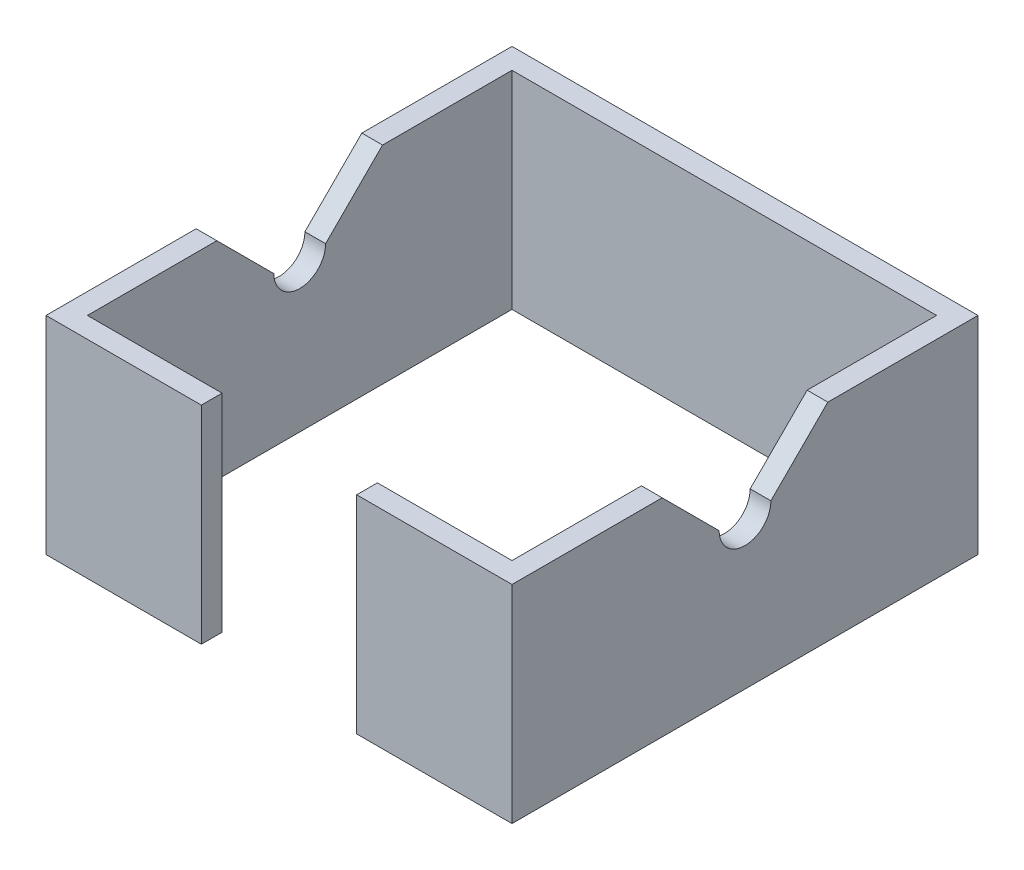
SolidWorks part; units mm, degrees
ref_plane "Přední rovina" through (0, 0, 0) normal (0, 0, 1) x (1, 0, 0)
ref_plane "Horní rovina" through (0, 0, 0) normal (0, 1, 0) x (1, 0, 0)
ref_plane "Pravá rovina" through (0, 0, 0) normal (1, 0, 0) x (0, 0, -1)
sketch "Skica1" plane through (0, 0, 0) normal (0, 1, 0) x (1, 0, 0)
  line L0 (2, -2) -> (43, -2)
  line L1 (0, 0) -> (45, 0)
  line L2 (0, 0) -> (0, -45)
  line L3 (0, -45) -> (45, -45)
  line L4 (45, 0) -> (45, -45)
  line L5 (43, -2) -> (43, -43)
  line L6 (2, -43) -> (43, -43)
  line L7 (2, -2) -> (2, -43)
  dimension "D1" = 45
  dimension "D2" = 45
  dimension "D3" = 2
extrude "Přidat vysunutím1" add sketch "Skica1" along normal blind 20
sketch "Skica2" plane through (0, 0, 45) normal (0, 0, 1) x (1, 0, 0)
  line L0 (0, 0) -> (45, 20) construction
  line L1 (45, 20) -> (45, 0) construction
  line L2 (0, 20) -> (45, 20) construction
  line L3 (0, 20) -> (45, 0) construction
  line L4 (0, 0) -> (45, 0) construction
  line L5 (15, 20) -> (30, 20)
  line L6 (15, 20) -> (15, 0)
  line L7 (15, 0) -> (30, 0)
  line L8 (30, 20) -> (30, 0)
  line L9 (15, 20) -> (30, 0) construction
  line L10 (15, 0) -> (30, 20) construction
  point P11 (22.5, 10)
  dimension "D1" = 15
extrude "Odebrat vysunutím1" cut sketch "Skica2" against normal up to next
sketch "Skica3" plane through (0, 0, 0) normal (-1, 0, 0) x (0, 0, 1)
  line L0 (22.5, 20) -> (22.5, 0) construction
  line L1 (0, 20) -> (45, 20) construction
  line L2 (0, 0) -> (45, 0) construction
  line L3 (20, 14.5) -> (25, 14.5)
  line L4 (20, 14.5) -> (14.5, 20)
  line L5 (25, 14.5) -> (30.5, 20)
  line L6 (14.5, 20) -> (30.5, 20)
  circle A0 centre (22.5, 14.5) radius 2.5
  line M7 (45, 20) -> (0, 20)
  dimension "D1" = 5
  dimension "D2" = 5.5
  dimension "D3" = 0
  dimension "D4" = 45
extrude "Odebrat vysunutím2" cut sketch "Skica3" against normal through all both and the other way through all contours L3 L0 A0 | L0 L3 A0 | L0 A0 L3 | A0 L0 L3 | L0 A0 L5 M7 | L0 L6 L4 A0
